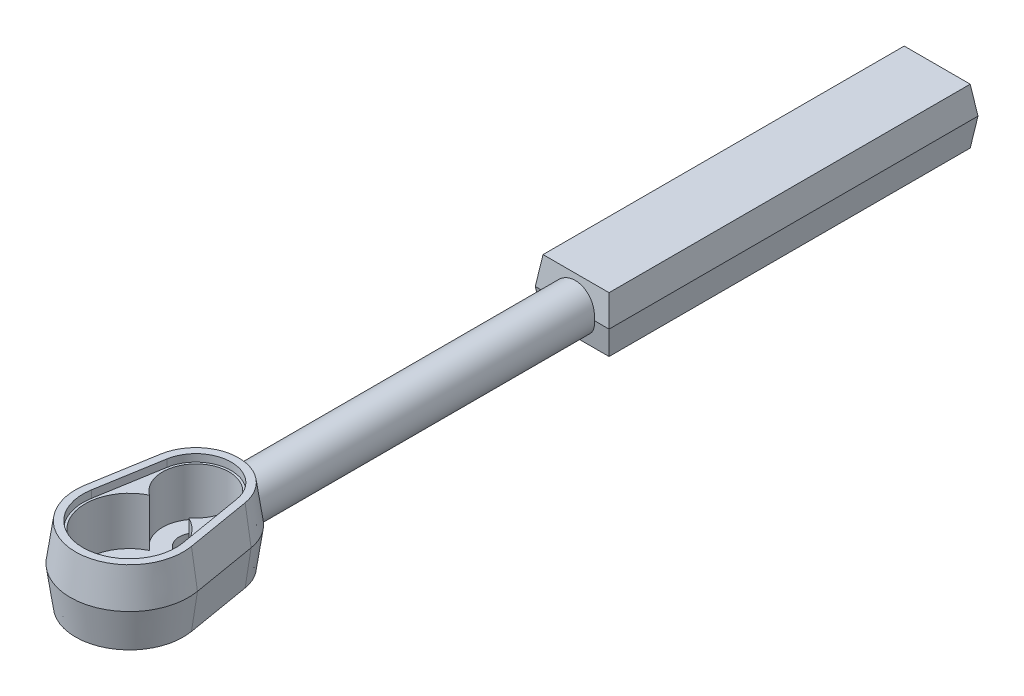
SolidWorks part; units mm, degrees
ref_plane "Front Plane" through (0, 0, 0) normal (0, 0, 1) x (1, 0, 0)
ref_plane "Top Plane" through (0, 0, 0) normal (0, 1, 0) x (1, 0, 0)
ref_plane "Right Plane" through (0, 0, 0) normal (1, 0, 0) x (0, 0, -1)
sketch "Croquis1" plane through (0, 0, 0) normal (0, 1, 0) x (1, 0, 0)
  line L0 (0, 0) -> (0, 220) construction
  line L1 (-10, 220) -> (10, 220)
  line L2 (10, 220) -> (10, 120)
  line L3 (10, 120) -> (-10, 120)
  line L4 (-10, 220) -> (-10, 120)
  point P7 (0, 120)
  dimension "D1" = 220
  dimension "D2" = 100
  dimension "D3" = 20
extrude "Mango" add sketch "Croquis1" along normal mid plane 15 draft 8
sketch "Croquis2" plane through (0, 0, 0) normal (0, 0, 1) x (1, 0, 0)
  circle A0 centre (0, 0) radius 6
  dimension "D1" = 12
extrude "Transicion" add sketch "Croquis2" against normal up to next
sketch "Croquis3" plane through (0, 0, 0) normal (0, 1, 0) x (1, 0, 0)
  line L0 (0, 0) -> (0, 18) construction
  line L1 (12.8182, 20.1667) -> (15.7762, 2.6667)
  line L2 (-15.7762, 2.6667) -> (-12.8182, 20.1667)
  arc A0 (15.7762, 2.6667) -> (-15.7762, 2.6667) centre (0, 0) cw
  arc A1 (-12.8182, 20.1667) -> (12.8182, 20.1667) centre (0, 18) cw
  point P5 (0, 0)
  point P8 (0, 0)
  point P10 (0.1066, 18)
  point P11 (0, 0)
  point P12 (2.0137, 24.1639)
  point P13 (0, 0)
  point P14 (0, 0)
  point P15 (0, 0)
  dimension "D2" = 13
  dimension "D3" = 16
  dimension "D1" = 18
extrude "Saliente-Extruir3" add sketch "Croquis3" along normal mid plane 20 draft 8
sketch "Croquis4" plane through (0, 10, 0) normal (0, 1, 0) x (1, 0, 0)
  line L4 (-9.4604, 19.5991) -> (-12.4184, 2.0991)
  line L5 (12.4184, 2.0991) -> (9.4604, 19.5991)
  line L6 (-9.4604, 19.5991) -> (-12.4184, 2.0991)
  line L7 (12.4184, 2.0991) -> (9.4604, 19.5991)
  arc A4 (9.4604, 19.5991) -> (-9.4604, 19.5991) centre (0, 18) ccw
  arc A5 (-12.4184, 2.0991) -> (12.4184, 2.0991) centre (0, 0) ccw
  arc A6 (9.4604, 19.5991) -> (-9.4604, 19.5991) centre (0, 18) ccw
  arc A7 (-12.4184, 2.0991) -> (12.4184, 2.0991) centre (0, 0) ccw
  dimension "D1" = 2
extrude "Cortar-Extruir1" cut sketch "Croquis4" against normal blind 2 contours A6 L6 A7 L7
sketch "Croquis5" plane through (0, 8, 0) normal (0, 1, 0) x (1, 0, 0)
  arc A0 (5.3327, 10.75) -> (-5.3327, 10.75) centre (0, 18) ccw
  arc A1 (-5.3327, 10.75) -> (5.3327, 10.75) centre (0, 0) ccw
  arc A2 (-12.4184, 2.0991) -> (12.4184, 2.0991) centre (0, 0) ccw construction
  dimension "D1" = 24
  dimension "D2" = 18
extrude "Cortar-Extruir2" cut sketch "Croquis5" against normal offset from surface (13 mm away) 5 up to face at (0, -10, -9.3412)
sketch "Croquis6" plane through (0, -5, 0) normal (0, 1, 0) x (1, 0, 0)
  circle A0 centre (0, 18) radius 4.5
  dimension "D1" = 9
extrude "Cortar-Extruir3" cut sketch "Croquis6" against normal blind 5 contours A0
sketch "Croquis7" plane through (0, -5, 0) normal (0, 1, 0) x (1, 0, 0)
  circle A0 centre (0, 0) radius 6
  point P3 (0, 0)
  point P5 (0, 0)
  point P7 (0, 0)
  dimension "D1" = 12
extrude "Cortar-Extruir4" cut sketch "Croquis7" against normal blind 5 contours A0
